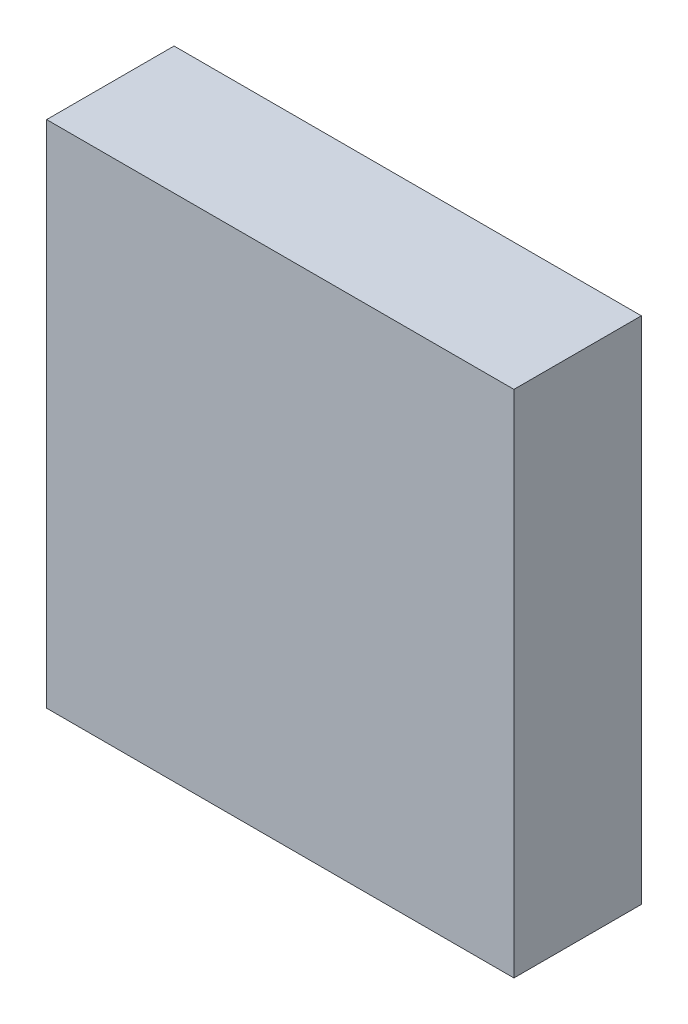
SolidWorks part; units mm, degrees
ref_plane "Front Plane" through (0, 0, 0) normal (0, 0, 1) x (1, 0, 0)
ref_plane "Top Plane" through (0, 0, 0) normal (0, 1, 0) x (1, 0, 0)
ref_plane "Right Plane" through (0, 0, 0) normal (1, 0, 0) x (0, 0, -1)
sketch "Sketch1" plane through (0, 0, 0) normal (0, 0, 1) x (1, 0, 0)
  line L5 (-5.5, -6) -> (5.5, -6)
  line L6 (-5.5, -6) -> (-5.5, 6)
  line L7 (-5.5, 6) -> (5.5, 6)
  line L8 (5.5, -6) -> (5.5, 6)
  line L9 (-5.5, -6) -> (5.5, 6) construction
  line L10 (-5.5, 6) -> (5.5, -6) construction
  point P0 (0, 0)
  dimension "D1" = 11
  dimension "D3" = 12
extrude "Boss-Extrude1" add sketch "Sketch1" along normal blind 3
